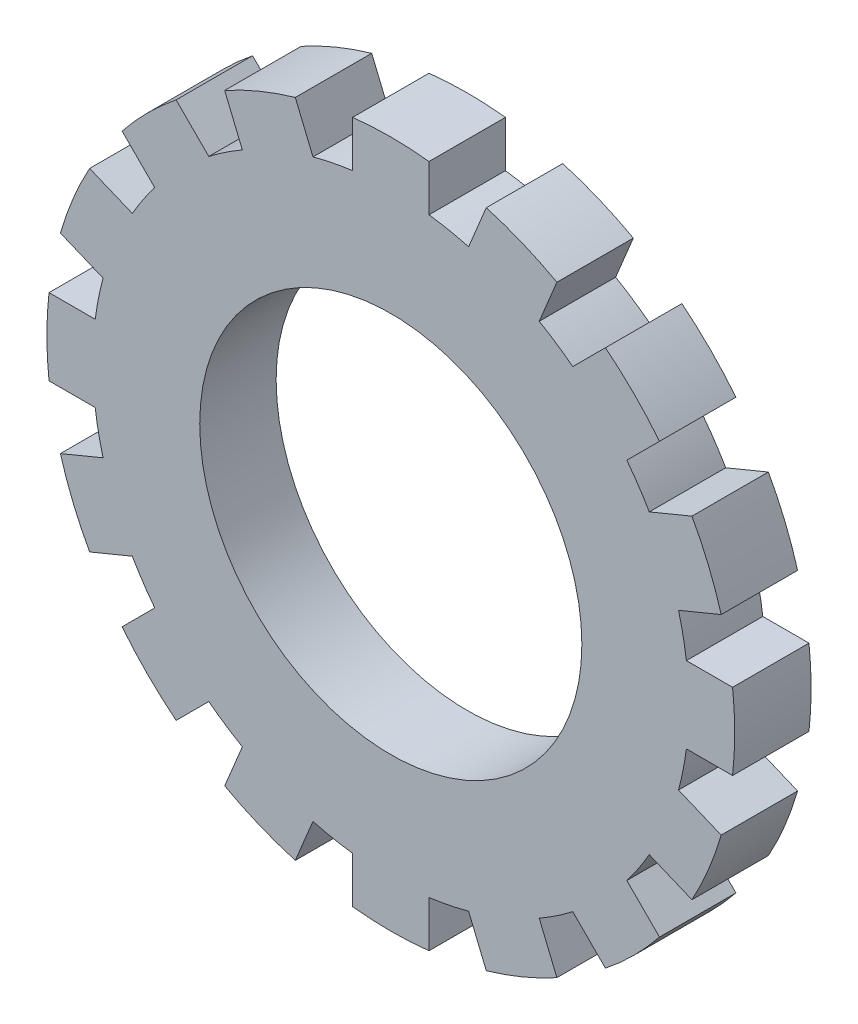
SolidWorks part; units mm, degrees
ref_plane "Front Plane" through (0, 0, 0) normal (0, 0, 1) x (1, 0, 0)
ref_plane "Top Plane" through (0, 0, 0) normal (0, 1, 0) x (1, 0, 0)
ref_plane "Right Plane" through (0, 0, 0) normal (1, 0, 0) x (0, 0, -1)
sketch "Sketch2" plane through (0, 0, 0) normal (0, 0, 1) x (1, 0, 0)
  line L0 (-55.0872, 0) -> (57.1639, 0) construction
  line L1 (1.0384, 51.6062) -> (1.0384, -58.2047) construction
  line L2 (38.6782, 5) -> (44.7214, 5)
  line L3 (38.6782, -5) -> (44.7214, -5)
  line L4 (33.8205, -19.4209) -> (39.4037, -21.7335)
  line L5 (37.6474, -10.1821) -> (43.2306, -12.4947)
  line L6 (23.8141, -30.8851) -> (28.0872, -35.1583)
  line L7 (30.8851, -23.8141) -> (35.1583, -28.0872)
  line L8 (10.1821, -37.6474) -> (12.4947, -43.2306)
  line L9 (19.4209, -33.8205) -> (21.7335, -39.4037)
  line L10 (-5, -38.6782) -> (-5, -44.7214)
  line L11 (5, -38.6782) -> (5, -44.7214)
  line L12 (-19.4209, -33.8205) -> (-21.7335, -39.4037)
  line L13 (-10.1821, -37.6474) -> (-12.4947, -43.2306)
  line L14 (-30.8851, -23.8141) -> (-35.1583, -28.0872)
  line L15 (-23.8141, -30.8851) -> (-28.0872, -35.1583)
  line L16 (-37.6474, -10.1821) -> (-43.2306, -12.4947)
  line L17 (-33.8205, -19.4209) -> (-39.4037, -21.7335)
  line L18 (-38.6782, 5) -> (-44.7214, 5)
  line L19 (-38.6782, -5) -> (-44.7214, -5)
  line L20 (-33.8205, 19.4209) -> (-39.4037, 21.7335)
  line L21 (-37.6474, 10.1821) -> (-43.2306, 12.4947)
  line L22 (-23.8141, 30.8851) -> (-28.0872, 35.1583)
  line L23 (-30.8851, 23.8141) -> (-35.1583, 28.0872)
  line L24 (-10.1821, 37.6474) -> (-12.4947, 43.2306)
  line L25 (-19.4209, 33.8205) -> (-21.7335, 39.4037)
  line L26 (5, 38.6782) -> (5, 44.7214)
  line L27 (-5, 38.6782) -> (-5, 44.7214)
  line L28 (19.4209, 33.8205) -> (21.7335, 39.4037)
  line L29 (10.1821, 37.6474) -> (12.4947, 43.2306)
  line L30 (30.8851, 23.8141) -> (35.1583, 28.0872)
  line L31 (23.8141, 30.8851) -> (28.0872, 35.1583)
  line L32 (37.6474, 10.1821) -> (43.2306, 12.4947)
  line L33 (33.8205, 19.4209) -> (39.4037, 21.7335)
  arc A0 (-37.6474, 10.1821) -> (-38.6782, 5) centre (0, 0) ccw
  circle A1 centre (0, 0) radius 25
  arc A2 (-39.4037, 21.7335) -> (-43.2306, 12.4947) centre (0, 0) ccw
  arc A3 (-44.7214, 5) -> (-44.7214, -5) centre (0, 0) ccw
  arc A4 (-28.0872, 35.1583) -> (-35.1583, 28.0872) centre (0, 0) ccw
  arc A5 (-12.4947, 43.2306) -> (-21.7335, 39.4037) centre (0, 0) ccw
  arc A6 (5, 44.7214) -> (-5, 44.7214) centre (0, 0) ccw
  arc A7 (21.7335, 39.4037) -> (12.4947, 43.2306) centre (0, 0) ccw
  arc A8 (35.1583, 28.0872) -> (28.0872, 35.1583) centre (0, 0) ccw
  arc A9 (43.2306, 12.4947) -> (39.4037, 21.7335) centre (0, 0) ccw
  arc A10 (44.7214, -5) -> (44.7214, 5) centre (0, 0) ccw
  arc A11 (-43.2306, -12.4947) -> (-39.4037, -21.7335) centre (0, 0) ccw
  arc A12 (-35.1583, -28.0872) -> (-28.0872, -35.1583) centre (0, 0) ccw
  arc A13 (-21.7335, -39.4037) -> (-12.4947, -43.2306) centre (0, 0) ccw
  arc A14 (-5, -44.7214) -> (5, -44.7214) centre (0, 0) ccw
  arc A15 (39.4037, -21.7335) -> (43.2306, -12.4947) centre (0, 0) ccw
  arc A16 (28.0872, -35.1583) -> (35.1583, -28.0872) centre (0, 0) ccw
  arc A17 (12.4947, -43.2306) -> (21.7335, -39.4037) centre (0, 0) ccw
  arc A18 (-30.8851, 23.8141) -> (-33.8205, 19.4209) centre (0, 0) ccw
  arc A19 (-19.4209, 33.8205) -> (-23.8141, 30.8851) centre (0, 0) ccw
  arc A20 (-5, 38.6782) -> (-10.1821, 37.6474) centre (0, 0) ccw
  arc A21 (10.1821, 37.6474) -> (5, 38.6782) centre (0, 0) ccw
  arc A22 (23.8141, 30.8851) -> (19.4209, 33.8205) centre (0, 0) ccw
  arc A23 (33.8205, 19.4209) -> (30.8851, 23.8141) centre (0, 0) ccw
  arc A24 (38.6782, 5) -> (37.6474, 10.1821) centre (0, 0) ccw
  arc A25 (-38.6782, -5) -> (-37.6474, -10.1821) centre (0, 0) ccw
  arc A26 (-33.8205, -19.4209) -> (-30.8851, -23.8141) centre (0, 0) ccw
  arc A27 (-23.8141, -30.8851) -> (-19.4209, -33.8205) centre (0, 0) ccw
  arc A28 (-10.1821, -37.6474) -> (-5, -38.6782) centre (0, 0) ccw
  arc A29 (5, -38.6782) -> (10.1821, -37.6474) centre (0, 0) ccw
  arc A30 (19.4209, -33.8205) -> (23.8141, -30.8851) centre (0, 0) ccw
  arc A31 (30.8851, -23.8141) -> (33.8205, -19.4209) centre (0, 0) ccw
  arc A32 (37.6474, -10.1821) -> (38.6782, -5) centre (0, 0) ccw
  dimension "D1" = 50
  dimension "D2" = 78
  dimension "D3" = 90
  dimension "D4" = 10
  dimension "D5" = 5
  dimension "D6" = 16
extrude "Boss-Extrude1" add sketch "Sketch2" along normal blind 10
